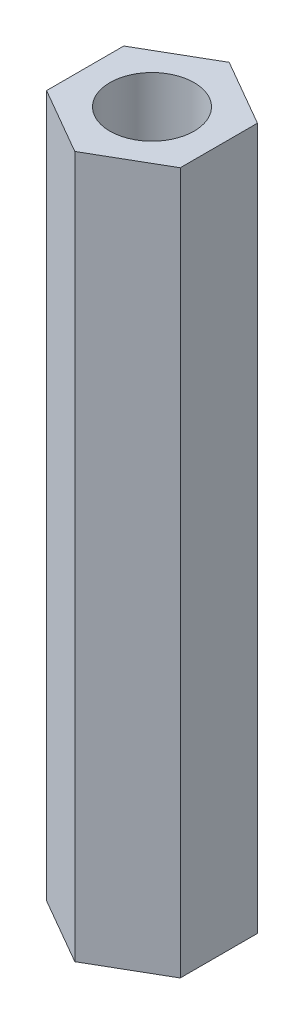
SolidWorks part; units mm, degrees
material "黄铜"
ref_plane "前视基准面" through (0, 0, 0) normal (0, 0, 1) x (1, 0, 0)
ref_plane "上视基准面" through (0, 0, 0) normal (0, 1, 0) x (1, 0, 0)
ref_plane "右视基准面" through (0, 0, 0) normal (1, 0, 0) x (0, 0, -1)
other "Configuration Table"
sketch "草图1" plane through (0, 0, 0) normal (0, 1, 0) x (1, 0, 0)
  line L1 (0, 2.75) -> (-2.3816, 1.375)
  line L2 (-2.3816, 1.375) -> (-2.3816, -1.375)
  line L3 (-2.3816, -1.375) -> (0, -2.75)
  line L4 (0, -2.75) -> (2.3816, -1.375)
  line L5 (2.3816, -1.375) -> (2.3816, 1.375)
  line L6 (2.3816, 1.375) -> (0, 2.75)
  circle A0 centre (0, 0) radius 1.5
  circle A1 centre (0, 0) radius 2.3816 construction
  dimension "D1" = 3
  dimension "D2" = 5.5
extrude "凸台-拉伸1" add sketch "草图1" along normal blind 25
